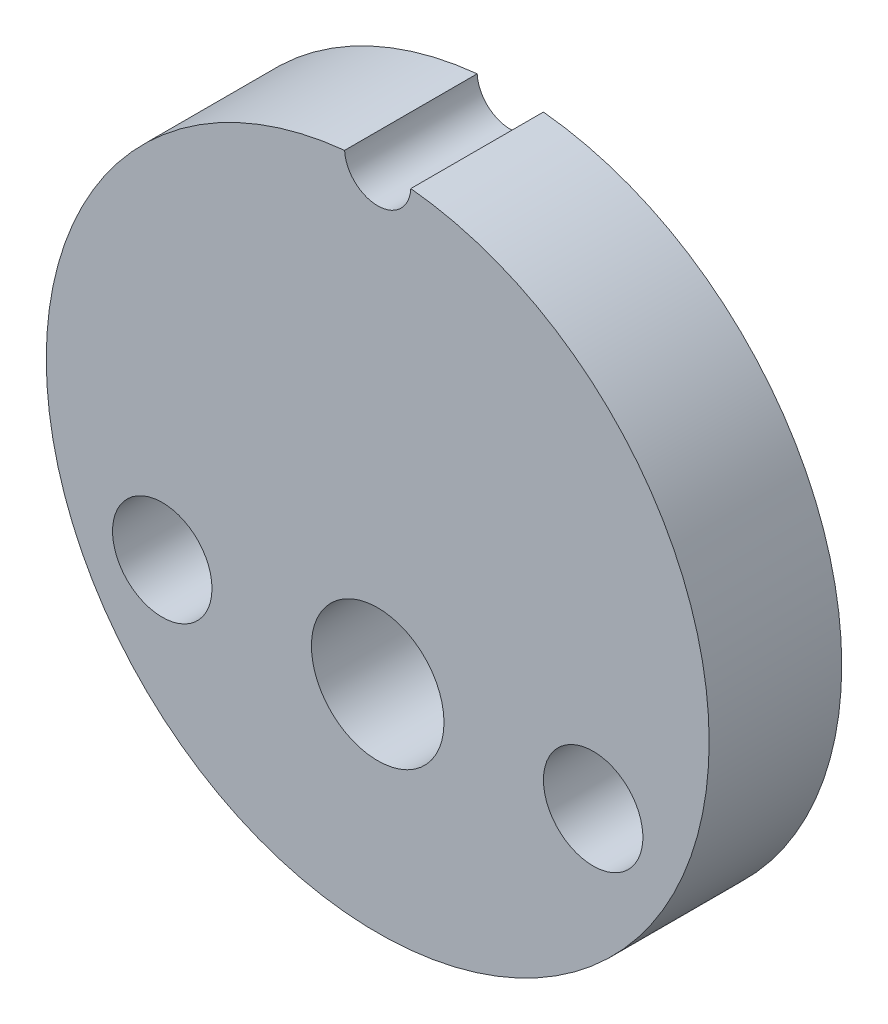
SolidWorks part; units mm, degrees
ref_plane "前视基准面" through (0, 0, 0) normal (0, 0, 1) x (1, 0, 0)
ref_plane "上视基准面" through (0, 0, 0) normal (0, 1, 0) x (1, 0, 0)
ref_plane "右视基准面" through (0, 0, 0) normal (1, 0, 0) x (0, 0, -1)
sketch "草图1" plane through (0, 0, 0) normal (0, 0, 1) x (1, 0, 0)
  line L0 (-0.5899, 5.3428) -> (-0.5899, 1.8428) construction
  line L1 (-0.5899, 1.8428) -> (-7.0899, 1.8428) construction
  circle A1 centre (-7.0899, 1.8428) radius 1.5
  circle A2 centre (5.9101, 1.8428) radius 1.5
  circle A3 centre (-0.5899, 1.8428) radius 2
  circle A4 centre (-0.5899, 5.3428) radius 10
  dimension "D1" = 3.5
  dimension "D2" = 6.5
extrude "凸台-拉伸1" add sketch "草图1" along normal blind 4 contours A4
sketch "草图2" plane through (0, 0, 4) normal (0, 0, 1) x (1, 0, 0)
  circle A0 centre (-0.5899, 15.3428) radius 1
  circle A1 centre (-0.5899, 5.3428) radius 10 construction
extrude "切除-拉伸1" cut sketch "草图2" against normal blind 10
